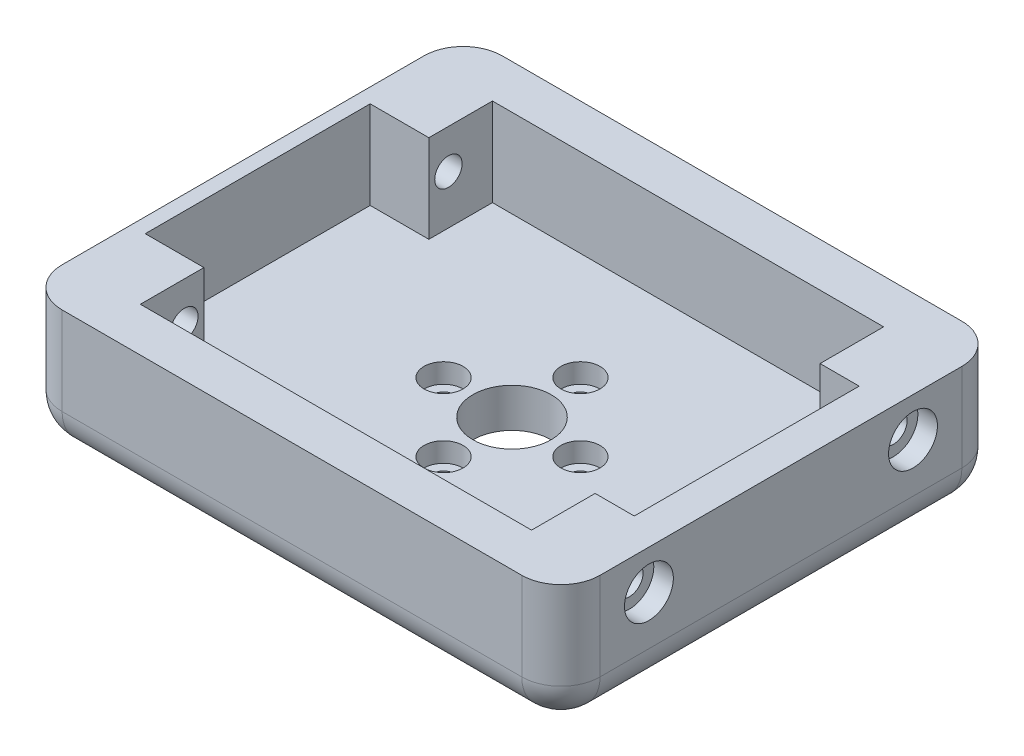
SolidWorks part; units mm, degrees
material "Esun Hard Tough Resin"
ref_plane "Front Plane" through (0, 0, 0) normal (0, 0, 1) x (1, 0, 0)
ref_plane "Top Plane" through (0, 0, 0) normal (0, 1, 0) x (1, 0, 0)
ref_plane "Right Plane" through (0, 0, 0) normal (1, 0, 0) x (0, 0, -1)
sketch "Sketch1" plane through (0, 0, 0) normal (0, 1, 0) x (1, 0, 0)
  line L1 (27.5, -22.5) -> (-27.5, -22.5)
  line L2 (27.5, -22.5) -> (27.5, 22.5)
  line L3 (27.5, 22.5) -> (-27.5, 22.5)
  line L4 (-27.5, -22.5) -> (-27.5, 22.5)
  line L5 (27.5, -22.5) -> (-27.5, 22.5) construction
  line L6 (27.5, 22.5) -> (-27.5, -22.5) construction
  point P0 (0, 0)
  dimension "D1" = 45
  dimension "D2" = 55
extrude "Boss-Extrude1" add sketch "Sketch1" along normal blind 13
sketch "Sketch2" plane through (0, 13, 0) normal (0, 1, 0) x (1, 0, 0)
  line L1 (20, -18) -> (-20, -18)
  line L2 (20, -18) -> (20, 18)
  line L3 (20, 18) -> (-20, 18)
  line L4 (-20, -18) -> (-20, 18)
  line L5 (20, -18) -> (-20, 18) construction
  line L6 (20, 18) -> (-20, -18) construction
  line L7 (-20, 11.5) -> (-26, 11.5)
  line L8 (-20, 11.5) -> (-20, -11.5)
  line L9 (-20, -11.5) -> (-26, -11.5)
  line L10 (-26, 11.5) -> (-26, -11.5)
  line L11 (20, 11.5) -> (24, 11.5)
  line L12 (20, 11.5) -> (20, -11.5)
  line L13 (20, -11.5) -> (24, -11.5)
  line L14 (24, 11.5) -> (24, -11.5)
  point P0 (0, 0)
  point P14 (24, 0)
  point P15 (-26, 0)
  dimension "D1" = 36
  dimension "D2" = 40
  dimension "D3" = 23
  dimension "D4" = 6
  dimension "D5" = 4
extrude "Cut-Extrude1" cut sketch "Sketch2" against normal offset from surface (9 mm away) 4 contours L4 L1 L2 L3 | L7 L10 L9 L4 | L14 L11 L2 L13 up to face at (0, 0, 0)
sketch "Sketch3" plane through (-27.5, 0, 0) normal (-1, 0, 0) x (0, 0, 1)
  line L0 (-22.5, 0) -> (22.5, 0) construction
  line L1 (-13.5, 9) -> (13.5, 9) construction
  circle A0 centre (-13.5, 9) radius 1.4
  circle A1 centre (13.5, 9) radius 1.4
  point P4 (0, 9)
  dimension "D2" = 2.8
  dimension "D1" = 27
  dimension "D3" = 9
extrude "Cut-Extrude2" cut sketch "Sketch3" against normal through all
sketch "Sketch4" plane through (0, 4, 0) normal (0, 1, 0) x (1, 0, 0)
  line L0 (-7, 0) -> (7, 0) construction
  line L2 (0, 7) -> (0, -7) construction
  circle A0 centre (0, 0) radius 7 construction
  circle A1 centre (0, 7) radius 1.05
  circle A2 centre (7, 0) radius 1.05
  circle A3 centre (-7, 0) radius 1.05
  circle A4 centre (0, -7) radius 1.05
  circle A5 centre (0, 0) radius 4
  dimension "D1" = 14
  dimension "D2" = 2.1
  dimension "D3" = 8
extrude "Cut-Extrude3" cut sketch "Sketch4" against normal through all
sketch "Sketch5" plane through (0, 4, 0) normal (0, 1, 0) x (1, 0, 0)
  circle A0 centre (-7, 0) radius 2
  circle A1 centre (0, 7) radius 2
  circle A2 centre (7, 0) radius 2
  circle A3 centre (0, -7) radius 2
  circle A4 centre (0, -7) radius 1.05 construction
  circle A5 centre (-7, 0) radius 1.05 construction
  circle A6 centre (0, 7) radius 1.05 construction
  circle A7 centre (7, 0) radius 1.05 construction
  dimension "D1" = 4
extrude "Cut-Extrude4" cut sketch "Sketch5" against normal blind 2
sketch "Sketch6" plane through (-27.5, 0, 0) normal (-1, 0, 0) x (0, 0, 1)
  circle A0 centre (-13.5, 9) radius 2.5
  circle A1 centre (13.5, 9) radius 2.5
  circle A2 centre (13.5, 9) radius 1.4 construction
  circle A3 centre (-13.5, 9) radius 1.4 construction
  dimension "D1" = 5
extrude "Cut-Extrude5" cut sketch "Sketch6" against normal blind 1.4
sketch "Sketch7" plane through (27.5, 0, 0) normal (1, 0, 0) x (0, 0, -1)
  circle A0 centre (-13.5, 9) radius 2.5
  circle A1 centre (13.5, 9) radius 2.5
  dimension "D1" = 5
extrude "Cut-Extrude6" cut sketch "Sketch7" against normal blind 2
fillet "Fillet1" radius 4 8 edges at (-27.5, 0, 0) (27.5, 0, 0) (0, 0, -22.5) (27.5, 6.5, -22.5) (-27.5, 6.5, -22.5) (0, 0, 22.5) (-27.5, 6.5, 22.5) (27.5, 6.5, 22.5)
